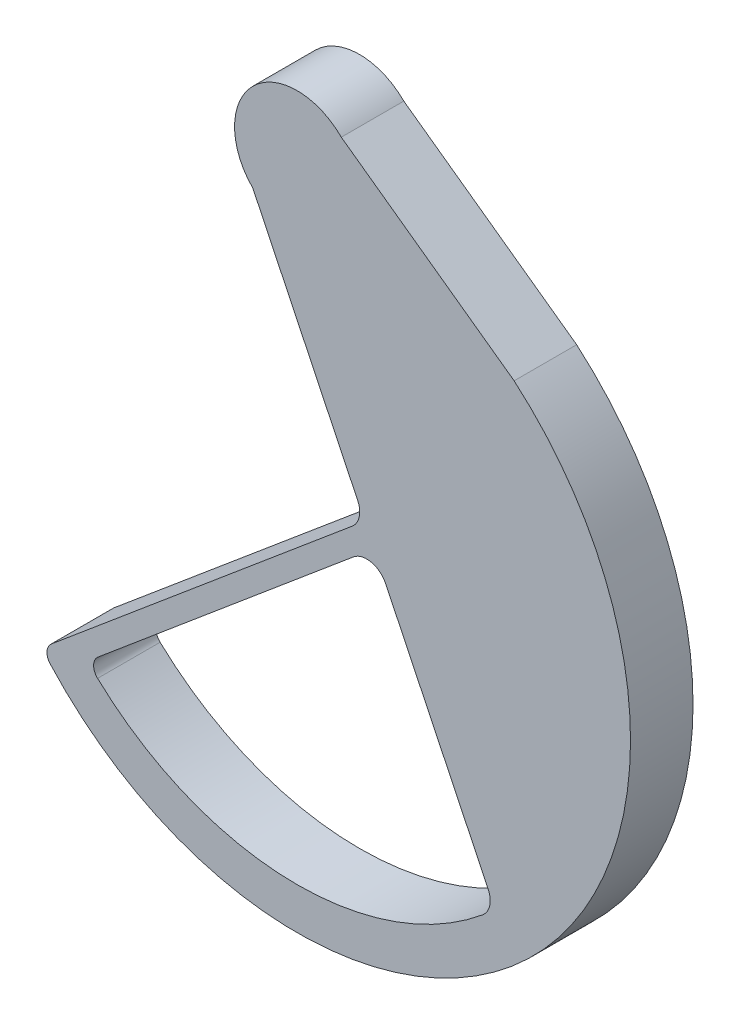
SolidWorks part; units mm, degrees
ref_plane "正面" through (0, 0, 0) normal (0, 0, 1) x (1, 0, 0)
ref_plane "平面" through (0, 0, 0) normal (0, 1, 0) x (1, 0, 0)
ref_plane "右側面" through (0, 0, 0) normal (1, 0, 0) x (0, 0, -1)
sketch "ｽｹｯﾁ4" plane through (0, 0, 0) normal (0, 0, 1) x (1, 0, 0)
  line L0 (0, 0.7897) -> (0, 0)
  line L1 (-53.6231, -124.9951) -> (-58.9406, -129.4571)
  line L3 (-10.6066, -10.6066) -> (14.5363, -62.8896)
  line L4 (-53.6231, -124.9951) -> (13.2442, -68.8868)
  line L5 (21.2324, -76.8138) -> (45.8448, -127.9938)
  line L6 (10.6066, 10.6066) -> (52.0762, -19.2705)
  line L7 (-58.0696, -135.2532) -> (-57.9498, -135.1527)
  line L8 (-47.7477, -126.5866) -> (13.5112, -75.1515)
  arc A1 (-59.2335, -133.7716) -> (52.0762, -19.2705) centre (0, -80) ccw
  arc A2 (-47.8702, -131.073) -> (44.5187, -134.0193) centre (0, -80) ccw
  arc A3 (10.6066, 10.6066) -> (-10.6066, -10.6066) centre (0, 0) ccw
  arc A4 (-59.2335, -133.7716) -> (-58.9406, -129.4571) centre (-57.0123, -131.7552) cw
  arc A5 (-47.8702, -131.073) -> (-47.7477, -126.5866) centre (-45.8186, -128.8841) cw
  arc A6 (13.5112, -75.1515) -> (21.2324, -76.8138) centre (16.7264, -78.9807) cw
  arc A7 (13.2442, -68.8868) -> (14.5363, -62.8896) centre (10.0302, -65.0566) ccw
  arc A8 (45.8448, -127.9938) -> (44.5187, -134.0193) centre (41.3388, -130.1608) cw
  point P18 (-61.2836, -131.423)
  point P21 (-50.2744, -128.7081)
  point P24 (18.4421, -71.0114)
  dimension "D3" = 140
  dimension "D4" = 30
  dimension "D5" = 5
  dimension "D6" = 3
  dimension "D7" = 3
  dimension "D8" = 5
  dimension "D9" = 5
  dimension "D10" = 5
  dimension "D2" = 5
extrude "ﾎﾞｽ - 押し出し1" add sketch "ｽｹｯﾁ4" along normal blind 15
sketch "ｽｹｯﾁ9" plane through (0, 0, 0) normal (0, 0, -1) x (-1, 0, 0)
  circle A0 centre (0, 0) radius 10
  dimension "D1" = 20
extrude "ｶｯﾄ - 押し出し3" cut sketch "ｽｹｯﾁ9" against normal blind 2
